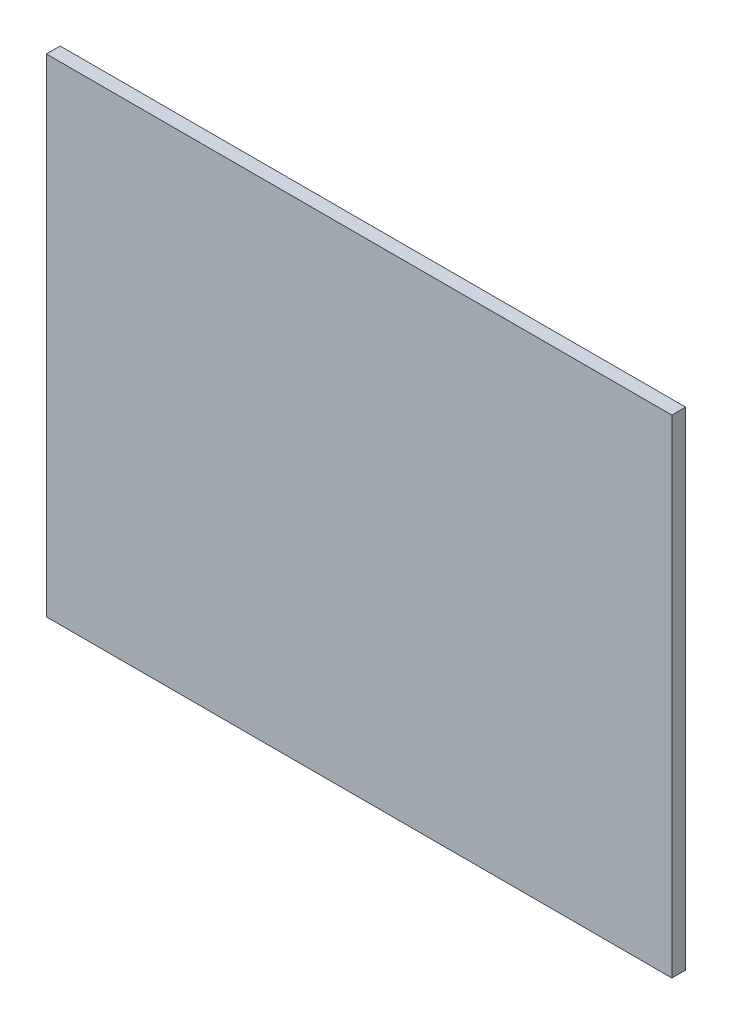
SolidWorks part; units mm, degrees
ref_plane "Front Plane" through (0, 0, 0) normal (0, 0, 1) x (1, 0, 0)
ref_plane "Top Plane" through (0, 0, 0) normal (0, 1, 0) x (1, 0, 0)
ref_plane "Right Plane" through (0, 0, 0) normal (1, 0, 0) x (0, 0, -1)
sketch "Sketch1" plane through (0, 0, 0) normal (0, 0, 1) x (1, 0, 0)
  line L1 (34, -26.5) -> (-34, -26.5)
  line L2 (34, -26.5) -> (34, 26.5)
  line L3 (34, 26.5) -> (-34, 26.5)
  line L4 (-34, -26.5) -> (-34, 26.5)
  line L5 (34, -26.5) -> (-34, 26.5) construction
  line L6 (34, 26.5) -> (-34, -26.5) construction
  point P0 (0, 0)
  dimension "D1" = 68
  dimension "D2" = 53
extrude "Boss-Extrude1" add sketch "Sketch1" along normal blind 1.5
